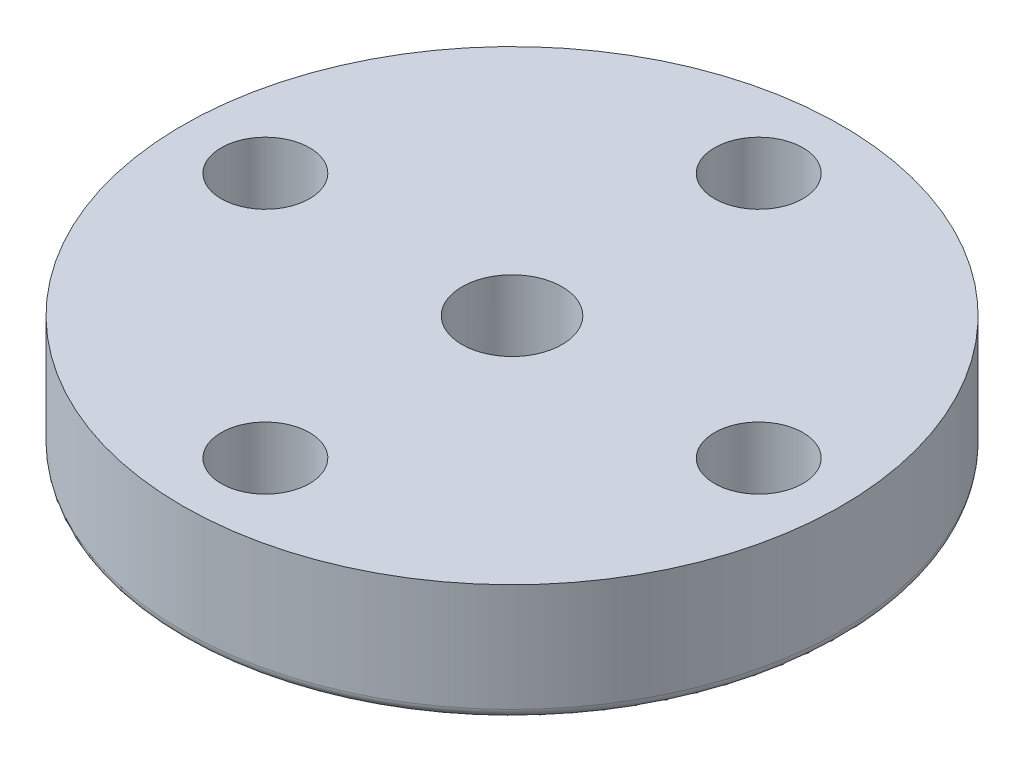
SolidWorks part; units mm, degrees
material "ABS"
ref_plane "Front Plane" through (0, 0, 0) normal (0, 0, 1) x (1, 0, 0)
ref_plane "Top Plane" through (0, 0, 0) normal (0, 1, 0) x (1, 0, 0)
ref_plane "Right Plane" through (0, 0, 0) normal (1, 0, 0) x (0, 0, -1)
sketch "Sketch1" plane through (0, 0, 0) normal (0, 1, 0) x (1, 0, 0)
  circle A0 centre (0, 0) radius 8.39
  dimension "D1" = 16.78
extrude "Boss-Extrude1" add sketch "Sketch1" along normal blind 3
sketch "Sketch2" plane through (0, 0, 0) normal (0, 1, 0) x (1, 0, 0)
  circle A0 centre (0, 0) radius 4.5
  dimension "D1" = 9
extrude "Boss-Extrude2" add sketch "Sketch2" against normal blind 2.5
sketch "Sketch3" plane through (0, 0, 0) normal (0, 1, 0) x (1, 0, 0)
  line L0 (0, 16.6668) -> (0, -17.2828) construction
  line L1 (-21.9372, 0) -> (30.2192, 0) construction
  line L2 (-6.28, 16.6668) -> (-6.28, -16.6668) construction
  line L3 (-15.9139, 6.28) -> (17.4197, 6.28) construction
  circle A0 centre (0, 6.28) radius 1.125
  circle A1 centre (-6.28, 0) radius 1.125
  circle A2 centre (0, -6.28) radius 1.125
  circle A3 centre (6.28, 0) radius 1.125
  dimension "D3" = 2.25
  dimension "D4" = 2.25
  dimension "D1" = 6.28
  dimension "D2" = 6.28
extrude "Cut-Extrude1" cut sketch "Sketch3" along normal through all
cosmetic thread "Cosmetic Thread1" parameters "D2"=2.87
cosmetic thread "Cosmetic Thread2" parameters "D2"=2.87
cosmetic thread "Cosmetic Thread3" parameters "D2"=2.87
cosmetic thread "Cosmetic Thread4" parameters "D2"=2.87
fillet "Fillet1" radius 0.25 1 edges at (0, 0, 8.39)
sketch "Sketch6" plane through (0, 3, 0) normal (0, 1, 0) x (1, 0, 0)
  circle A0 centre (0, 0) radius 1.275
  dimension "D1" = 2.55
extrude "Cut-Extrude2" cut sketch "Sketch6" against normal through all
sketch "Sketch7" plane through (0, -2.5, 0) normal (0, -1, 0) x (1, 0, 0)
  circle A0 centre (0, 0) radius 3.11
  dimension "D1" = 6.22
extrude "Cut-Extrude3" cut sketch "Sketch7" against normal blind 2.5
sketch3d "3DSketch1"
  line L0 (0, 0, 0) -> (0, -47.4119, 0) construction
sketch "Sketch8" plane through (0, -2.5, 0) normal (0, -1, 0) x (1, 0, 0)
  line L1 (2.5809, 1.0001) -> (2.972, 0.8801)
  line L2 (2.5809, 1.0001) -> (2.767, 1.3643)
  arc A1 (2.972, 0.8801) -> (2.767, 1.3643) centre (0.21, -0.0038) ccw
  circle A4 centre (0, 0) radius 3.11 construction
  dimension "D4" = 0.409
  dimension "D3" = 5.8
  dimension "D1" = 80
  dimension "D2" = 0.5258
extrude "Boss-Extrude4" add sketch "Sketch8" against normal blind 2.5
pattern_circular "CirPattern1" count 26 over 360 about axis through (0, 0, 0) along (0, 1, 0) of "Boss-Extrude4"
sketch "Croquis3" plane through (0, 0, 0) normal (0, -1, 0) x (1, 0, 0)
  circle A0 centre (0, 6.28) radius 2 construction
  dimension "D1" = 4
